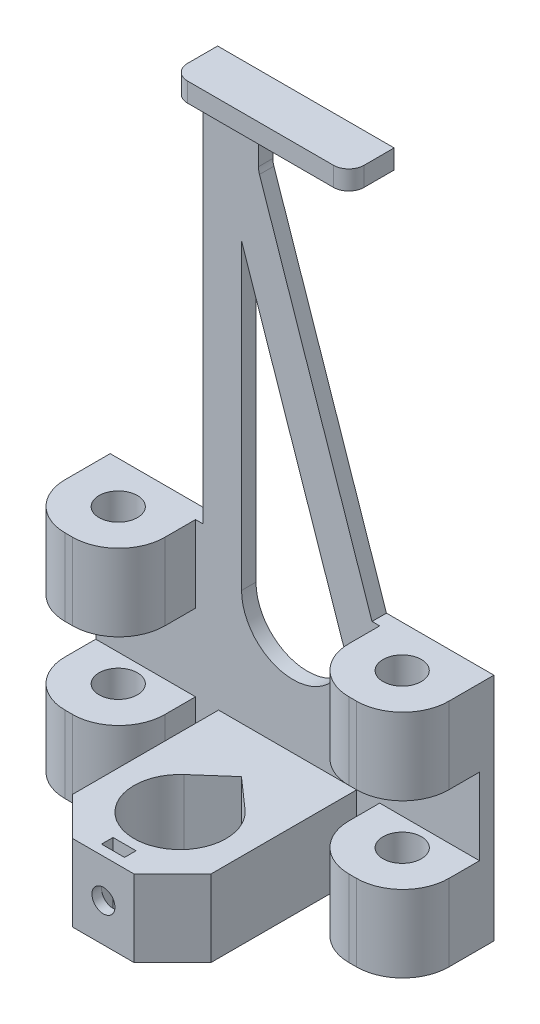
SolidWorks part; units mm, degrees
ref_plane "Alzado" through (0, 0, 0) normal (0, 0, 1) x (1, 0, 0)
ref_plane "Planta" through (0, 0, 0) normal (0, 1, 0) x (1, 0, 0)
ref_plane "Vista lateral" through (0, 0, 0) normal (1, 0, 0) x (0, 0, -1)
sketch "Croquis1" plane through (0, 0, 0) normal (0, 0, 1) x (1, 0, 0)
  line L0 (-11, 15) -> (-11, 68)
  line L1 (25, -15) -> (-25, -15)
  line L2 (25, -15) -> (25, 15)
  line L3 (25, 15) -> (11, 15)
  line L4 (-25, -15) -> (-25, 15)
  line L5 (25, -15) -> (-25, 15) construction
  line L6 (25, 15) -> (-25, -15) construction
  line L7 (-11, 68) -> (12, 68)
  line L8 (12, 68) -> (12, 65.5)
  line L9 (12, 65.5) -> (-1.3, 65.5)
  line L10 (-3.8, 63) -> (-3.8, 58.9136)
  line L11 (-3.6668, 58.1084) -> (11, 15)
  line L12 (-11, 15) -> (-25, 15)
  line L13 (-6, 10) -> (-6, 49.443)
  line L14 (-6, 49.443) -> (-6, 49.443)
  line L15 (-6, 49.443) -> (-6, 49.443)
  line L16 (-6, 49.443) -> (-6, 49.443)
  line L17 (-6, 49.443) -> (-6, 49.443)
  line L18 (-6, 49.443) -> (7.4197, 10)
  line L24 (-20, -10) -> (-20, 10) construction
  line L25 (-6, 10) -> (-20, 10) construction
  line L26 (20, 10) -> (7.4197, 10) construction
  line L27 (20, -10) -> (-20, -10) construction
  line L28 (20, -10) -> (20, 10) construction
  arc A0 (-3.8, 58.9136) -> (-3.6668, 58.1084) centre (-1.3, 58.9136) ccw
  arc A1 (-1.3, 65.5) -> (-3.8, 63) centre (-1.3, 63) ccw
  arc A2 (-6, 49.443) -> (-6, 49.443) centre (-6, 49.443) ccw
  arc A3 (-6, 49.443) -> (-6, 49.443) centre (-6, 49.443) ccw
  arc A4 (-6, 10) -> (7.4197, 10) centre (0.7098, 10) ccw
  point P0 (0, 0)
  point P17 (-3.8, 58.5)
  point P20 (-3.8, 65.5)
  dimension "D10" = 2.5
  dimension "D1" = 50
  dimension "D2" = 30
  dimension "D3" = 14
  dimension "D4" = 14
  dimension "D5" = 2.5
  dimension "D6" = 23
  dimension "D7" = 53
  dimension "D8" = 7.2
  dimension "D9" = 7
  dimension "D11" = 5
extrude "Saliente-Extruir1" add sketch "Croquis1" along normal blind 1.88
sketch "Croquis2" plane through (0, 0, 1.88) normal (0, 0, 1) x (1, 0, 0)
  line L0 (-1.3, 65.5) -> (-11, 65.5)
  line L11 (-11, 15) -> (-25, 15)
  line L12 (-25, 15) -> (-25, -15)
  line L13 (-25, -15) -> (25, -15)
  line L14 (25, -15) -> (25, 15)
  line L15 (25, 15) -> (11, 15)
  line L16 (11, 15) -> (-3.6668, 58.1084)
  line L17 (-3.8, 58.9136) -> (-3.8, 63)
  line L18 (-1.3, 65.5) -> (12, 65.5)
  line L19 (12, 65.5) -> (12, 68)
  line L20 (12, 68) -> (-11, 68)
  line L21 (-11, 68) -> (-11, 15)
  line L29 (-1.3, 65.5) -> (12, 65.5)
  line L30 (12, 65.5) -> (12, 68)
  line L31 (12, 68) -> (-11, 68)
  line L32 (-11, 68) -> (-11, 65.5)
  arc A2 (-3.8, 58.9136) -> (-3.6668, 58.1084) centre (-1.3, 58.9136) ccw
  arc A3 (-1.3, 65.5) -> (-3.8, 63) centre (-1.3, 63) ccw
  dimension "D1" = 0
extrude "Saliente-Extruir2" add sketch "Croquis2" along normal blind 4.03
fillet "Redondeo1" radius 2 2 edges at (12, 66.75, 5.91) (-11, 66.75, 5.91)
sketch "Croquis3" plane through (0, 0, 1.88) normal (0, 0, 1) x (1, 0, 0)
  line L0 (0, 0) -> (-25, 0) construction
  line L1 (-25, 15) -> (-12, 15)
  line L2 (-25, 15) -> (-25, 5)
  line L3 (-25, 5) -> (-12, 5)
  line L4 (-12, 15) -> (-12, 5)
  line L5 (-25, 15) -> (-25, -15) construction
  line L6 (0, 0) -> (0, -15) construction
  line L7 (-25, -15) -> (25, -15) construction
  line L8 (-25, -5) -> (-12, -5)
  line L9 (-12, -15) -> (-12, -5)
  line L10 (-25, -15) -> (-12, -15)
  line L11 (-25, -15) -> (-25, -5)
  line L12 (25, -15) -> (25, -5)
  line L13 (25, -15) -> (12, -15)
  line L14 (12, -15) -> (12, -5)
  line L15 (25, -5) -> (12, -5)
  line L16 (25, 5) -> (12, 5)
  line L17 (12, 15) -> (12, 5)
  line L18 (25, 15) -> (12, 15)
  line L19 (25, 15) -> (25, 5)
  dimension "D1" = 13
  dimension "D2" = 10
extrude "Saliente-Extruir3" add sketch "Croquis3" along normal blind 10
fillet "Redondeo2" radius 6 8 edges at (25, 10, 11.88) (12, 10, 11.88) (25, -10, 11.88) (12, -10, 11.88) (-12, -10, 11.88) (-25, -10, 11.88) (-12, 10, 11.88) (-25, 10, 11.88)
sketch "Croquis4" plane through (0, 0, 1.88) normal (0, 0, 1) x (1, 0, 0)
  line L0 (0, -15) -> (0, 0) construction
  line L1 (-12, -15) -> (12, -15) construction
  line L3 (-9, -15) -> (9, -15)
  line L4 (-9, -15) -> (-9, -5)
  line L5 (-9, -5) -> (9, -5)
  line L6 (9, -15) -> (9, -5)
  line L7 (-9, -15) -> (9, -5) construction
  line L8 (-9, -5) -> (9, -15) construction
  point P5 (0, -10)
  dimension "D1" = 10
  dimension "D2" = 18
extrude "Saliente-Extruir4" add sketch "Croquis4" along normal blind 24
chamfer "Chaflán1" distance 5 angle 45 2 edges at (-9, -10, 25.88) (9, -10, 25.88)
sketch "Croquis5" plane through (0, -5, 0) normal (0, 1, 0) x (1, 0, 0)
  line L0 (0, -25.88) -> (0, -5.91) construction
  line L1 (4, -25.88) -> (-4, -25.88) construction
  line L2 (10, -5.91) -> (-9, -5.91) construction
  line L3 (0, -7.895) -> (-3.9686, -11.395)
  line L4 (0, -7.895) -> (3.9686, -11.395)
  arc A0 (-3.9686, -11.395) -> (3.9686, -11.395) centre (0, -15.895) ccw
  dimension "D1" = 12
  dimension "D2" = 8
extrude "Cortar-Extruir1" cut sketch "Croquis5" against normal blind 24
sketch "Croquis6" plane through (0, 0, 25.88) normal (0, 0, 1) x (1, 0, 0)
  line L1 (0, -5) -> (0, -15) construction
  line L2 (9, -5) -> (-9, -5) construction
  line L3 (-4, -15) -> (4, -15) construction
  circle A0 centre (0, -10) radius 1.5
  dimension "D1" = 3
extrude "Cortar-Extruir2" cut sketch "Croquis6" against normal blind 14
sketch "Croquis7" plane through (0, -5, 0) normal (0, 1, 0) x (1, 0, 0)
  line L0 (4, -25.88) -> (-4, -25.88) construction
  line L1 (-1.5, -24.63) -> (1.5, -24.63)
  line L2 (-1.5, -24.63) -> (-1.5, -23.13)
  line L3 (-1.5, -23.13) -> (1.5, -23.13)
  line L4 (1.5, -24.63) -> (1.5, -23.13)
  line L5 (-1.5, -24.63) -> (1.5, -23.13) construction
  line L6 (-1.5, -23.13) -> (1.5, -24.63) construction
  point P0 (0, -23.88)
  dimension "D1" = 3
  dimension "D2" = 1.5
  dimension "D3" = 2
extrude "Cortar-Extruir3" cut sketch "Croquis7" against normal blind 14
sketch "Croquis8" plane through (0, 15, 0) normal (0, 1, 0) x (1, 0, 0)
  circle A0 centre (-18.5, -5.45) radius 2.5
  circle A1 centre (18.5, -5.45) radius 2.5
extrude "Cortar-Extruir4" cut sketch "Croquis8" against normal through all
